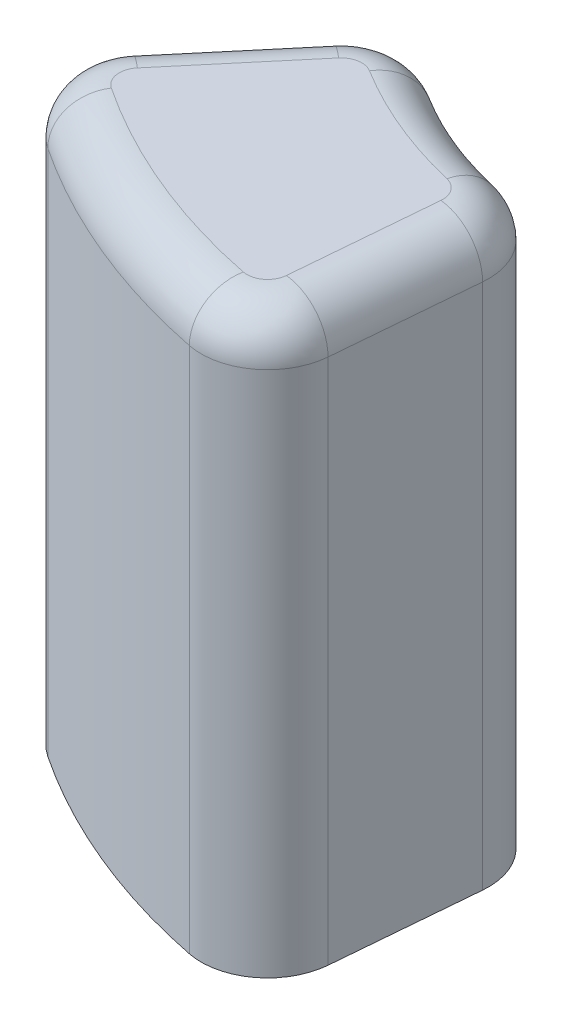
SolidWorks part; units mm, degrees
ref_plane "Front Plane" through (0, 0, 0) normal (0, 0, 1) x (1, 0, 0)
ref_plane "Top Plane" through (0, 0, 0) normal (0, 1, 0) x (1, 0, 0)
ref_plane "Right Plane" through (0, 0, 0) normal (1, 0, 0) x (0, 0, -1)
sketch "Sketch1" plane through (0, 0, 0) normal (0, 1, 0) x (-1, 0, 0)
  line L6 (1.7382, 20.2047) -> (2.2728, 26.4182) construction
  line L7 (13.0577, 15.516) -> (17.0734, 20.2876) construction
  line L21 (1.8379, 20.1961) -> (2.3724, 26.4097)
  line L23 (12.9812, 15.5804) -> (16.9969, 20.352)
  arc A12 (16.4395, 24.7173) -> (5.8533, 29.1022) centre (0, 0) ccw construction
  arc A31 (17.0734, 20.2876) -> (16.4395, 24.7173) centre (14.7781, 22.2193) ccw construction
  arc A32 (2.2728, 26.4182) -> (5.8533, 29.1022) centre (5.2617, 26.1611) cw construction
  arc A42 (9.1874, 14.8943) -> (4.0354, 17.0284) centre (0, 0) ccw construction
  arc A45 (1.7382, 20.2047) -> (4.0354, 17.0284) centre (4.7272, 19.9475) ccw construction
  arc A46 (13.0577, 15.516) -> (9.1874, 14.8943) centre (10.7624, 17.4477) cw construction
  arc A59 (2.3724, 26.4097) -> (5.8336, 29.0042) centre (5.2617, 26.1611) cw
  arc A60 (16.3841, 24.634) -> (5.8336, 29.0042) centre (0, 0) ccw
  arc A61 (16.9969, 20.352) -> (16.3841, 24.634) centre (14.7781, 22.2193) ccw
  arc A62 (12.9812, 15.5804) -> (9.2399, 14.9794) centre (10.7624, 17.4477) cw
  arc A63 (9.2399, 14.9794) -> (4.0585, 17.1257) centre (0, 0) ccw
  arc A64 (1.8379, 20.1961) -> (4.0585, 17.1257) centre (4.7272, 19.9475) ccw
  point P0 (0, 0)
  point P77 (1.5, 17.4356)
  dimension "D1" = 0.1
extrude "Boss-Extrude1" add sketch "Sketch1" along normal blind 25
fillet "Fillet1" radius 2 8 edges at (-11.2223, 25, 14.5844) (-6.7352, 25, 16.2603) (-2.3773, 25, 18.2481) (-2.1051, 25, 23.3029) (-3.5223, 25, 28.4815) (-11.3217, 25, 27.333) (-17.6488, 25, 22.6302) (-14.9891, 25, 17.9662)
